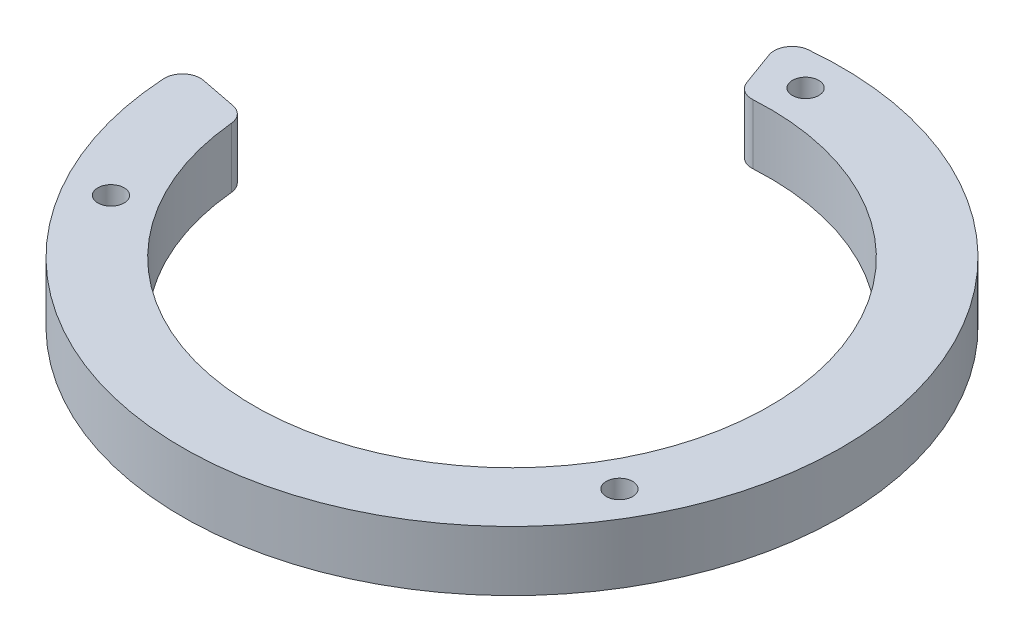
SolidWorks part; units mm, degrees
material "Thornel Mat VMA"
ref_plane "前视基准面" through (0, 0, 0) normal (0, 0, 1) x (1, 0, 0)
ref_plane "上视基准面" through (0, 0, 0) normal (0, 1, 0) x (1, 0, 0)
ref_plane "右视基准面" through (0, 0, 0) normal (1, 0, 0) x (0, 0, -1)
other "Configuration Table"
sketch "草图1" plane through (0, 0, 0) normal (0, 1, 0) x (1, 0, 0)
  circle A0 centre (0, 0) radius 27.5
  circle A1 centre (0, 0) radius 21.5
  circle A2 centre (0, 0) radius 24.5 construction
  circle A3 centre (0, 24.5) radius 1.1
  circle A4 centre (21.2176, -12.25) radius 1.1
  circle A5 centre (-21.2176, -12.25) radius 1.1
  point P7 (-48.0958, -12.7786)
  point P8 (0, 0)
  point P14 (0, 0)
  dimension "D1" = 43
  dimension "D2" = 55
  dimension "D3" = 49
  dimension "D4" = 2.2
  dimension "D5" = 3
extrude "凸台-拉伸1" add sketch "草图1" along normal blind 5
sketch "草图2" plane through (0, 0, 0) normal (0, -1, 0) x (1, 0, 0)
  line L0 (-21.0726, 0.9733) -> (-25.666, 0.0748) construction
  line L1 (-21.0726, 0.9733) -> (-25.666, 0.0748) construction
  line L2 (-3.9117, -25.3663) -> (-2.3109, -20.9681) construction
  line L3 (-3.9117, -25.3663) -> (-2.3109, -20.9681) construction
  line L4 (-2.4534, -21.3596) -> (-4.5503, -27.1209)
  line L5 (-21.4814, 0.8933) -> (-27.4985, -0.2836)
  circle A0 centre (0, 0) radius 27.5 construction
  circle A1 centre (0, 0) radius 21.5 construction
  arc A2 (-27.4985, -0.2836) -> (-4.5503, -27.1209) centre (0, 0) ccw
  arc A3 (-21.4814, 0.8933) -> (-2.4534, -21.3596) centre (0, 0) ccw
extrude "切除-拉伸1" cut sketch "草图2" against normal blind 5
fillet "圆角1" radius 1.5 4 edges at (-4.5503, 2.5, -27.1209) (-2.4534, 2.5, -21.3596) (-27.4985, 2.5, -0.2836) (-21.4814, 2.5, 0.8933)
